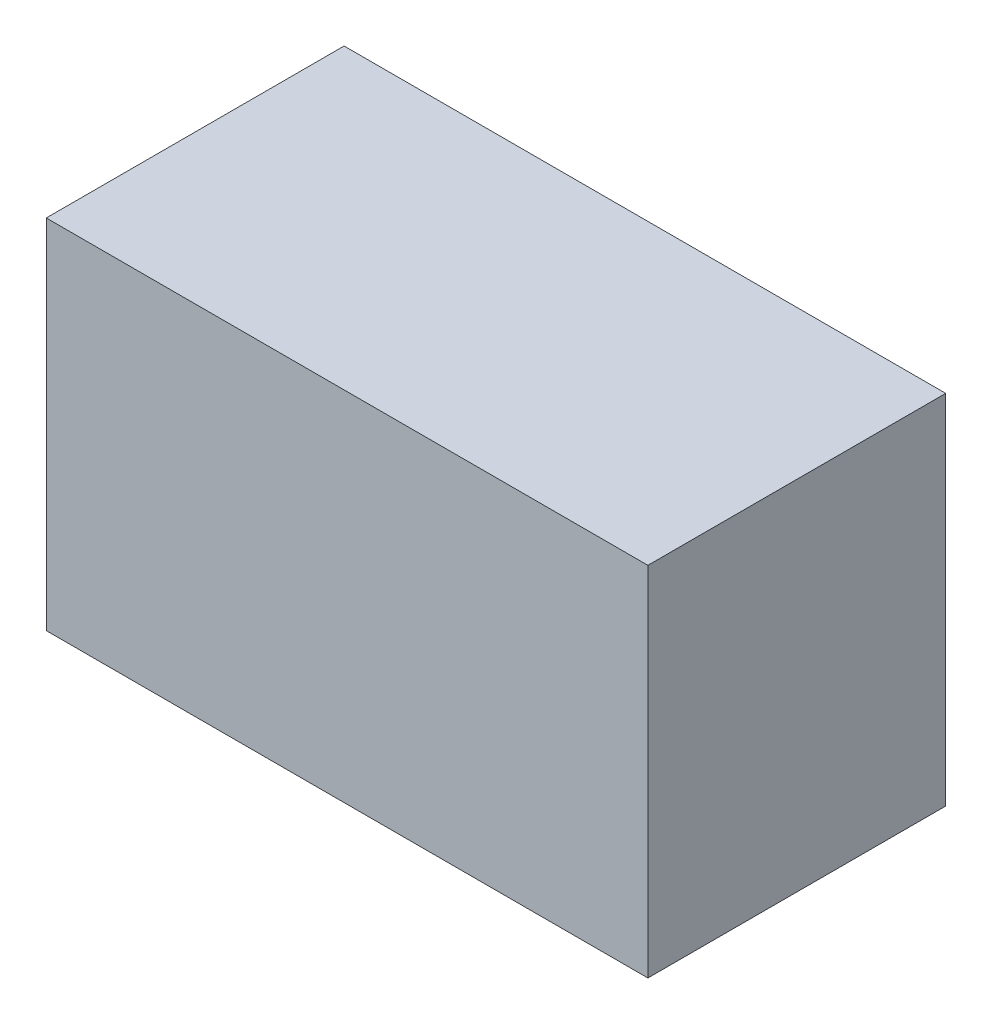
SolidWorks part; units mm, degrees
ref_plane "Alzado" through (0, 0, 0) normal (0, 0, 1) x (1, 0, 0)
ref_plane "Planta" through (0, 0, 0) normal (0, 1, 0) x (1, 0, 0)
ref_plane "Vista lateral" through (0, 0, 0) normal (1, 0, 0) x (0, 0, -1)
sketch "Croquis1" plane through (0, 0, 0) normal (0, 1, 0) x (1, 0, 0)
  line L1 (-10.1, 5) -> (10.1, 5)
  line L2 (-10.1, 5) -> (-10.1, -5)
  line L3 (-10.1, -5) -> (10.1, -5)
  line L4 (10.1, 5) -> (10.1, -5)
  line L5 (-10.1, 5) -> (10.1, -5) construction
  line L6 (-10.1, -5) -> (10.1, 5) construction
  point P0 (0, 0)
  dimension "D1" = 10
  dimension "D2" = 20.2
extrude "Saliente-Extruir1" add sketch "Croquis1" along normal blind 12
